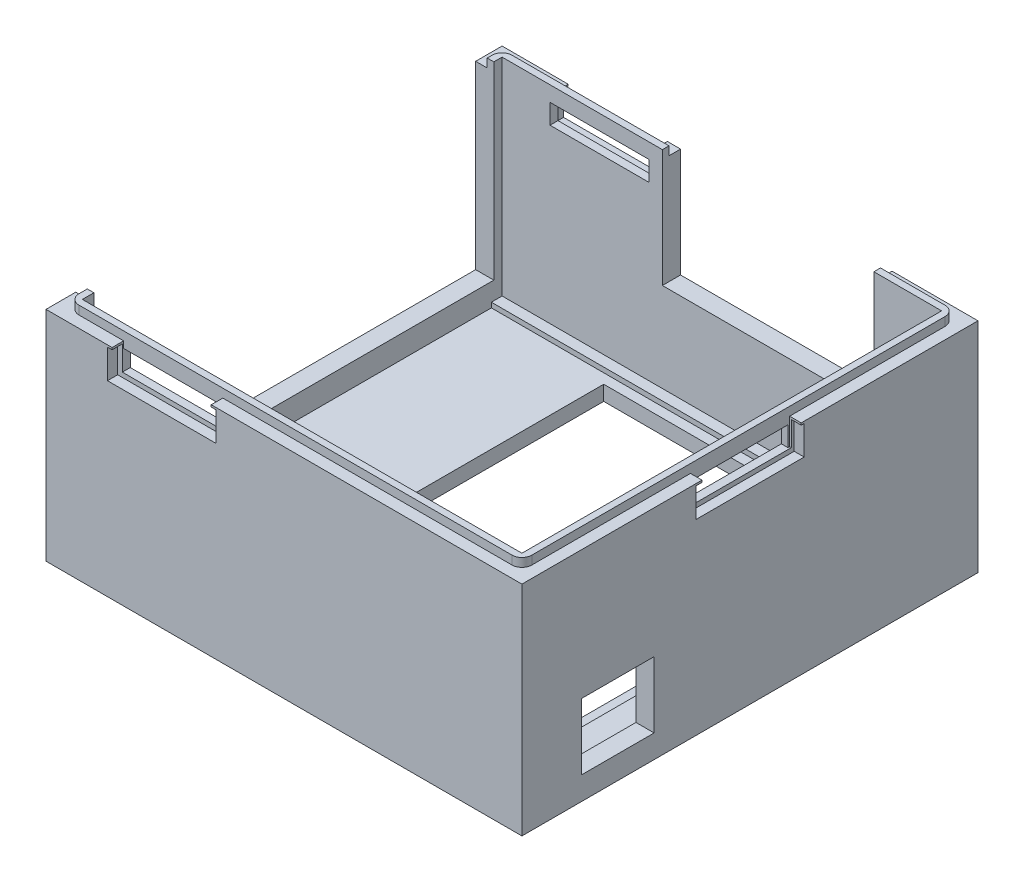
SolidWorks part; units mm, degrees
material "ABS"
ref_plane "Front Plane" through (0, 0, 0) normal (0, 0, 1) x (1, 0, 0)
ref_plane "Top Plane" through (0, 0, 0) normal (0, 1, 0) x (1, 0, 0)
ref_plane "Right Plane" through (0, 0, 0) normal (1, 0, 0) x (0, 0, -1)
sketch "Sketch2" plane through (0, 0, 0) normal (0, 1, 0) x (1, 0, 0)
  line L1 (-33.25, 31.75) -> (33.25, 31.75)
  line L2 (-33.25, 31.75) -> (-33.25, -31.75)
  line L3 (-33.25, -31.75) -> (33.25, -31.75)
  line L4 (33.25, 31.75) -> (33.25, -31.75)
  line L5 (-33.25, 31.75) -> (33.25, -31.75) construction
  line L6 (-33.25, -31.75) -> (33.25, 31.75) construction
  point P0 (0, 0)
  dimension "D1" = 66.5
  dimension "D2" = 63.5
extrude "Boss-Extrude1" add sketch "Sketch2" along normal blind 3
sketch "Sketch3" plane through (0, 3, 0) normal (0, 1, 0) x (1, 0, 0)
  line L0 (-33.25, 31.75) -> (-33.25, -31.75) construction
  line L1 (-33.25, 30.125) -> (29.25, 30.125)
  line L2 (-33.25, 30.125) -> (-33.25, -30.125)
  line L3 (-33.25, -30.125) -> (29.25, -30.125)
  line L4 (29.25, 30.125) -> (29.25, -30.125)
  dimension "D1" = 60.25
  dimension "D2" = 62.5
  dimension "D3" = 30.125
extrude "Cut-Extrude1" cut sketch "Sketch3" against normal blind 0.75
sketch "Sketch4" plane through (0, 2.25, 0) normal (0, 1, 0) x (1, 0, 0)
  line L0 (29.25, -30.125) -> (29.25, 30.125) construction
  line L1 (-14.75, 28.625) -> (27.25, 28.625)
  line L2 (-14.75, 28.625) -> (-14.75, -28.125)
  line L3 (-14.75, -28.125) -> (27.25, -28.125)
  line L4 (27.25, 28.625) -> (27.25, -28.125)
  line L5 (-33.25, -30.125) -> (29.25, -30.125) construction
  dimension "D1" = 56.75
  dimension "D2" = 42
  dimension "D3" = 2
  dimension "D4" = 2
extrude "Cut-Extrude2" cut sketch "Sketch4" against normal through all
sketch "Sketch6" plane through (0, 0, 0) normal (0, 1, 0) x (1, 0, 0)
  line L1 (-33.25, 31.75) -> (33.25, 31.75)
  line L2 (-33.25, 31.75) -> (-33.25, -31.75)
  line L3 (-33.25, -31.75) -> (33.25, -31.75)
  line L4 (33.25, 31.75) -> (33.25, -31.75)
  line L5 (-33.25, 31.75) -> (33.25, -31.75) construction
  line L6 (-33.25, -31.75) -> (33.25, 31.75) construction
  line L7 (-36, 34.5) -> (36, 34.5)
  line L8 (-36, 34.5) -> (-36, -34.5)
  line L9 (-36, -34.5) -> (36, -34.5)
  line L10 (36, 34.5) -> (36, -34.5)
  line L11 (-36, 34.5) -> (36, -34.5) construction
  line L12 (-36, -34.5) -> (36, 34.5) construction
  point P0 (0, 0)
  point P7 (0, 0)
  dimension "D1" = 2.75
  dimension "D2" = 2.75
extrude "Boss-Extrude2" add sketch "Sketch6" along normal blind 33
sketch "Sketch7" plane through (-36, 0, 0) normal (-1, 0, 0) x (0, 0, 1)
  line L0 (-1022.025, 3) -> (48977.975, 3) construction
  line L1 (-34.5, 0) -> (34.5, 0) construction
  line L2 (-1038.9209, 25) -> (48961.0791, 25) construction
  line L3 (30, 3) -> (30, 33)
  line L4 (-34.5, 33) -> (34.5, 33) construction
  line L5 (-30.5, 3) -> (-30.5, 33)
  line L6 (-30.5, 33) -> (30, 33)
  line L7 (34.5, 33) -> (34.5, 0) construction
  line L8 (-34.5, 33) -> (-34.5, 0) construction
  line L9 (-30.5, 3) -> (30, 3)
  dimension "D1" = 3
  dimension "D2" = 25
  dimension "D3" = 4.5
  dimension "D4" = 4
extrude "Cut-Extrude3" cut sketch "Sketch7" against normal blind 30
sketch "Sketch8" plane through (36, 0, 0) normal (1, 0, 0) x (0, 0, -1)
  line L0 (-1023.8353, 3.5) -> (48976.1647, 3.5) construction
  line L1 (-1023.5335, 13.5) -> (48976.4665, 13.5) construction
  line L2 (-34.5, 0) -> (34.5, 0) construction
  line L3 (-25.5, 3.5) -> (-25.5, 13.5)
  line L4 (-34.5, 33) -> (-34.5, 0) construction
  line L5 (-14.5, 3.5) -> (-14.5, 13.5)
  line L6 (-14.5, 13.5) -> (-25.5, 13.5)
  line L7 (-14.5, 3.5) -> (-25.5, 3.5)
  dimension "D1" = 3.5
  dimension "D2" = 13.5
  dimension "D3" = 9
  dimension "D4" = 11
extrude "Cut-Extrude4" cut sketch "Sketch8" against normal blind 3
sketch "Sketch10" plane through (0, 0, -34.5) normal (0, 0, -1) x (-1, 0, 0)
  line L0 (-1016.5425, 16.5) -> (48983.4575, 16.5) construction
  line L1 (-36, 0) -> (36, 0) construction
  line L2 (-23, 16.5) -> (-23, 33)
  line L3 (-36, 33) -> (36, 33) construction
  line L4 (9, 16.5) -> (9, 33)
  line L5 (-36, 33) -> (-36, 0) construction
  line L6 (-23, 16.5) -> (9, 16.5)
  line L7 (9, 33) -> (-23, 33)
  dimension "D1" = 16.5
  dimension "D2" = 13
  dimension "D3" = 45
extrude "Cut-Extrude5" cut sketch "Sketch10" against normal blind 16.5
sketch "Sketch11" plane through (0, 33, 0) normal (0, 1, 0) x (1, 0, 0)
  line L0 (-34.25, 31.25) -> (-34.25, 30.5)
  line L1 (-33.25, 31.75) -> (-9, 31.75)
  line L2 (-33.25, 31.75) -> (-33.25, 30.5)
  line L3 (-33.25, -31.75) -> (33.25, -31.75)
  line L4 (33.25, 31.75) -> (33.25, -31.75)
  line L5 (-33.25, 31.75) -> (33.25, -31.75) construction
  line L6 (-33.25, -31.75) -> (33.25, 31.75) construction
  line L7 (-32.75, -32.75) -> (32.75, -32.75)
  line L8 (34.25, 31.25) -> (34.25, -31.25)
  line L9 (-32.75, 32.75) -> (-9, 32.75)
  line L10 (23, 31.75) -> (23, 32.75)
  line L11 (23, 31.75) -> (23, 34.5) construction
  line L12 (-9, 31.75) -> (-9, 32.75)
  line L13 (-9, 31.75) -> (-9, 34.5) construction
  line L14 (-34.25, 30.5) -> (-33.25, 30.5)
  line L15 (-33.25, 30.5) -> (-36, 30.5) construction
  line L16 (-33.25, -30) -> (-34.25, -30)
  line L17 (-33.25, -30) -> (-36, -30) construction
  line L18 (23, 32.75) -> (32.75, 32.75)
  line L19 (-34.25, 32.75) -> (34.25, 32.75) construction
  line L20 (23, 31.75) -> (33.25, 31.75)
  line L21 (-33.25, 31.75) -> (33.25, 31.75) construction
  line L22 (-34.25, -30) -> (-34.25, -31.25)
  line L23 (-34.25, 32.75) -> (-34.25, -32.75) construction
  line L24 (-33.25, -30) -> (-33.25, -31.75)
  line L25 (-33.25, 31.75) -> (-33.25, -31.75) construction
  line L26 (-34.25, -32.75) -> (34.25, -32.75) construction
  line L27 (34.25, 32.75) -> (34.25, -32.75) construction
  arc A0 (32.75, -32.75) -> (34.25, -31.25) centre (32.75, -31.25) ccw
  arc A1 (-34.25, -31.25) -> (-32.75, -32.75) centre (-32.75, -31.25) ccw
  arc A2 (-34.25, 31.25) -> (-32.75, 32.75) centre (-32.75, 31.25) cw
  arc A3 (34.25, 31.25) -> (32.75, 32.75) centre (32.75, 31.25) ccw
  point P0 (0, 0)
  dimension "D2" = 1.5
  dimension "D1" = 1
extrude "Boss-Extrude3" add sketch "Sketch11" along normal blind 1.3
sketch "Sketch12" plane through (0, 0, 34.5) normal (0, 0, 1) x (1, 0, 0)
  line L0 (-1016.5168, 32) -> (48983.4832, 32) construction
  line L1 (-1015.0509, 29) -> (48984.9491, 29) construction
  line L2 (-36, 33) -> (36, 33) construction
  line L3 (-32.75, 33) -> (32.75, 33) construction
  line L4 (-26, 29) -> (-26, 32)
  line L5 (-26, 32) -> (-11, 32)
  line L6 (-11, 32) -> (-11, 29)
  line L7 (-11, 29) -> (-26, 29)
  line L8 (-36, 33) -> (-36, 0) construction
  line L9 (0, -1000) -> (0, 49000) construction
  line L10 (-36, 0) -> (36, 0) construction
  line L11 (26, 29) -> (26, 32) construction
  line L12 (11, 29) -> (26, 29) construction
  line L13 (26, 32) -> (11, 32) construction
  line L14 (11, 32) -> (11, 29) construction
  point P19 (0, 0)
  dimension "D1" = 1
  dimension "D2" = 4
  dimension "D3" = 10
  dimension "D4" = 25
extrude "Cut-Extrude6" cut sketch "Sketch12" against normal through all
sketch "Sketch13" plane through (36, 0, 0) normal (1, 0, 0) x (0, 0, -1)
  line L0 (-1026.5034, 32) -> (48973.4966, 32) construction
  line L1 (-1023.3931, 29) -> (48976.6069, 29) construction
  line L2 (-34.5, 33) -> (34.5, 33) construction
  line L3 (-34.5, 0) -> (34.5, 0) construction
  line L4 (-7.5, 29) -> (7.5, 29)
  line L5 (-7.5, 29) -> (-7.5, 32)
  line L6 (-7.5, 32) -> (7.5, 32)
  line L7 (7.5, 29) -> (7.5, 32)
  point P10 (0, 0)
  dimension "D1" = 1
  dimension "D2" = 4
  dimension "D3" = 15
  dimension "D4" = 7.5
extrude "Cut-Extrude7" cut sketch "Sketch13" against normal blind 3
sketch "Sketch14" plane through (0, 0, 34.5) normal (0, 0, 1) x (1, 0, 0)
  line L0 (-26, 32) -> (-26, 29) construction
  line L1 (-11, 32) -> (-26, 32) construction
  line L2 (-11, 29) -> (-11, 32) construction
  line L3 (-26, 29) -> (-11, 29) construction
  line L4 (-26, 32) -> (-26, 29)
  line L5 (-11, 32) -> (-26, 32)
  line L6 (-11, 29) -> (-11, 32)
  line L7 (-26, 29) -> (-11, 29)
  line L8 (-26.7, 32.7) -> (-26.7, 28.3)
  line L9 (-26.7, 28.3) -> (-10.3, 28.3)
  line L10 (-10.3, 28.3) -> (-10.3, 32.7)
  line L11 (-10.3, 32.7) -> (-26.7, 32.7)
  dimension "D1" = 0.7
extrude "Cut-Extrude9" cut sketch "Sketch14" against normal blind 1.55
sketch "Sketch15" plane through (0, 33, 0) normal (0, 1, 0) x (1, 0, 0)
  line L0 (-36, -34.5) -> (36, -34.5) construction
  line L1 (-26, -34.5) -> (-11, -34.5)
  line L2 (-26, -34.5) -> (-26, -32.75)
  line L3 (-26, -32.75) -> (-11, -32.75)
  line L4 (-11, -34.5) -> (-11, -32.75)
  line L5 (-32.75, -32.75) -> (32.75, -32.75) construction
  line L6 (-36, -30) -> (-36, -34.5) construction
  dimension "D1" = 10
  dimension "D2" = 15
extrude "Cut-Extrude10" cut sketch "Sketch15" against normal blind 4
mirror "Mirror1" about plane through (0, 0, 0) normal (0, 0, 1) of "Cut-Extrude10", "Cut-Extrude9"
sketch "Sketch17" plane through (36, 0, 0) normal (1, 0, 0) x (0, 0, -1)
  line L0 (-7.5, 32) -> (-7.5, 29) construction
  line L1 (7.5, 32) -> (-7.5, 32) construction
  line L2 (7.5, 29) -> (7.5, 32) construction
  line L3 (-7.5, 29) -> (7.5, 29) construction
  line L4 (-7.5, 32) -> (-7.5, 29)
  line L5 (7.5, 32) -> (-7.5, 32)
  line L6 (7.5, 29) -> (7.5, 32)
  line L7 (-7.5, 29) -> (7.5, 29)
  line L8 (-8.2, 32.7) -> (-8.2, 28.3)
  line L9 (-8.2, 28.3) -> (8.2, 28.3)
  line L10 (8.2, 28.3) -> (8.2, 32.7)
  line L11 (8.2, 32.7) -> (-8.2, 32.7)
  dimension "D1" = 0.7
extrude "Cut-Extrude12" cut sketch "Sketch17" against normal blind 1.5
sketch "Sketch16" plane through (0, 33, 0) normal (0, 1, 0) x (1, 0, 0)
  line L0 (34.25, -31.25) -> (34.25, 31.25) construction
  line L1 (34.25, -7.25) -> (36, -7.25)
  line L2 (34.25, -7.25) -> (34.25, 7.75)
  line L3 (34.25, 7.75) -> (36, 7.75)
  line L4 (36, -7.25) -> (36, 7.75)
  line L5 (36, -34.5) -> (36, 34.5) construction
  line L6 (-36, 30.5) -> (-36, -30) construction
  point P8 (-36, 0.25)
  dimension "D1" = 15
  dimension "D2" = 7.5
extrude "Cut-Extrude11" cut sketch "Sketch16" against normal blind 4
sketch "Sketch18" plane through (0, 0, 0) normal (0, -1, 0) x (1, 0, 0)
  line L0 (-14.75, 28.125) -> (27.25, 28.125) construction
  line L1 (-7.75, 28.125) -> (20.25, 28.125)
  line L2 (-7.75, 28.125) -> (-7.75, 31.125)
  line L3 (-7.75, 31.125) -> (20.25, 31.125)
  line L4 (20.25, 28.125) -> (20.25, 31.125)
  line L5 (-14.75, -28.625) -> (-14.75, 28.125) construction
  line L6 (27.25, 28.125) -> (27.25, -28.625) construction
  dimension "D1" = 7
  dimension "D2" = 7
  dimension "D3" = 3
extrude "Cut-Extrude13" cut sketch "Sketch18" against normal blind 3
sketch "Sketch20" plane through (0, 3, 0) normal (0, 1, 0) x (1, 0, 0)
  line L0 (-33.25, -30) -> (-33.25, 30.125) construction
  line L1 (-36, 30.5) -> (-33.25, 30.5)
  line L2 (-36, 30.5) -> (-36, -30)
  line L3 (-36, -30) -> (-33.25, -30)
  line L4 (-33.25, 30.5) -> (-33.25, -30)
extrude "Boss-Extrude4" add sketch "Sketch20" along normal blind 2.7
equation "\"D3@Sketch3\"=\"D1@Sketch3\"/2"
